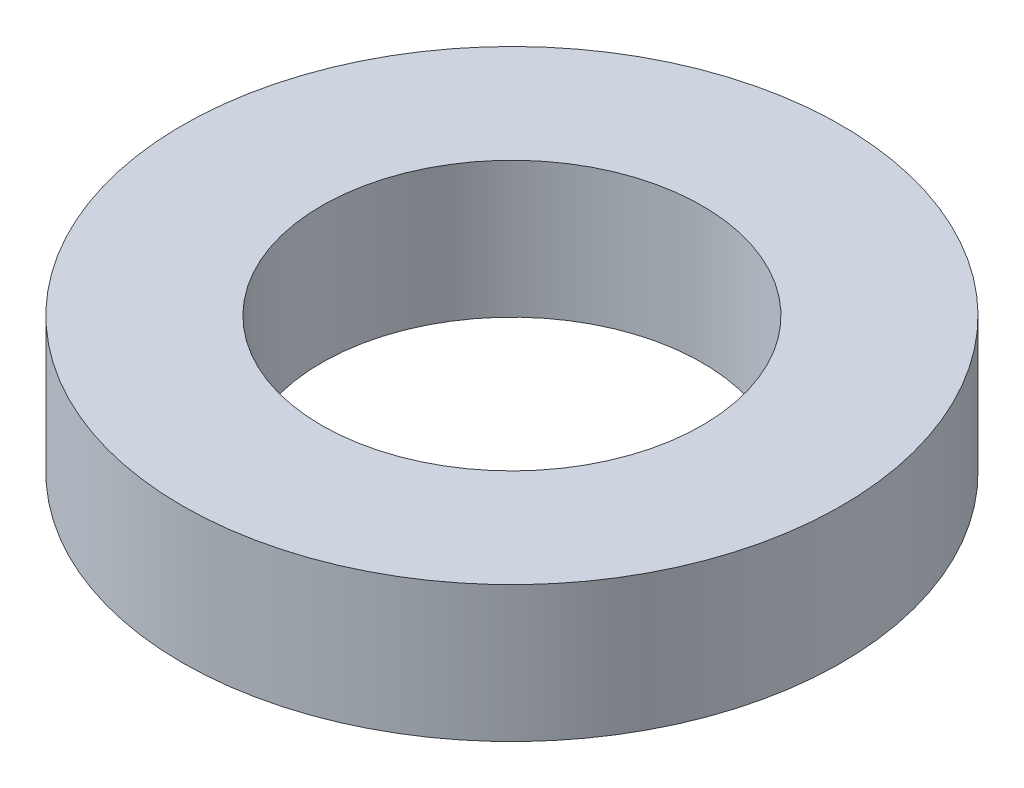
SolidWorks part; units mm, degrees
material "Rubber"
ref_plane "Front Plane" through (0, 0, 0) normal (0, 0, 1) x (1, 0, 0)
ref_plane "Top Plane" through (0, 0, 0) normal (0, 1, 0) x (1, 0, 0)
ref_plane "Right Plane" through (0, 0, 0) normal (1, 0, 0) x (0, 0, -1)
other "Configuration Table"
sketch "Sketch1" plane through (0, 0, 0) normal (0, 1, 0) x (1, 0, 0)
  circle A0 centre (0, 0) radius 2.8
  circle A1 centre (0, 0) radius 4.85
  dimension "D1" = 5.6
  dimension "D2" = 9.7
extrude "O_Ring" add sketch "Sketch1" along normal blind 2 from offset 1
equation "\"Jar_OD\"= 90  'ASSUMED - Part G fallback - jar outer diameter"
equation "\"Jar_H\"= 120  'ASSUMED - Part G fallback - jar height"
equation "\"Pump_L\"= 45  'ASSUMED - Part G fallback"
equation "\"Pump_W\"= 24  'ASSUMED - Part G fallback"
equation "\"Pump_H\"= 33  'ASSUMED - Part G fallback"
equation "\"Pump_Outlet_OD\"= 7.5  'ASSUMED - Part G fallback"
equation "\"Tube_OD\"= 8  'ASSUMED - Part G fallback"
equation "\"Tube_ID\"= 6  'ASSUMED - Part G fallback"
equation "\"TDS_Body_Dia\"= 12  'ASSUMED - Part G fallback"
equation "\"TDS_Wet_Len\"= 45  'ASSUMED - Part G fallback - length in water"
equation "\"DS_Tube_Dia\"= 6  'ASSUMED - Part G fallback"
equation "\"DS_Tube_Len\"= 50  'ASSUMED - Part G fallback"
equation "\"ORP_Body_Dia\"= 12  'ASSUMED - Part G fallback"
equation "\"ORP_Body_Len\"= 150  'ASSUMED - Part G fallback"
equation "\"ORP_Cap_Dia\"= 16  'ASSUMED - Part G fallback"
equation "\"Turb_W\"= 33  'ASSUMED - Part G fallback - head width"
equation "\"Turb_D\"= 28  'ASSUMED - Part G fallback - head depth"
equation "\"Turb_H\"= 30  'ASSUMED - Part G fallback - head height"
equation "\"Turb_Slot_W\"= 10  'ASSUMED - Part G fallback - slot width"
equation "\"Flow_L\"= 62  'ASSUMED - Part G fallback YF-S201"
equation "\"Flow_W\"= 36  'ASSUMED - Part G fallback"
equation "\"Flow_H\"= 35  'ASSUMED - Part G fallback"
equation "\"Thread_G12_OD\"= 20.955  'ASSUMED - Part G fallback thread G1/2 (major diameter)"
equation "\"Valve_L\"= 75  'ASSUMED - Part G fallback"
equation "\"Valve_W\"= 45  'ASSUMED - Part G fallback"
equation "\"Valve_H\"= 60  'ASSUMED - Part G fallback"
equation "\"Tee_L\"= 40  'ASSUMED - Part G fallback - overall length"
equation "\"Tee_Branch_L\"= 25  'ASSUMED - Part G fallback"
equation "\"Tee_OD\"= 12  'ASSUMED - Part G fallback"
equation "\"Cuv_W\"= 12.5  'ASSUMED - old R3 cuvette (station suppressed in SS4)"
equation "\"Cuv_D\"= 12.5  'ASSUMED - old R3 cuvette (station suppressed in SS4)"
equation "\"Cuv_H\"= 45  'ASSUMED - old R3 cuvette (station suppressed in SS4)"
equation "\"LED_Board_L\"= 20  'ASSUMED - Part G fallback"
equation "\"LED_Board_W\"= 20  'ASSUMED - Part G fallback - LED at centre"
equation "\"GUVA_L\"= 20  'ASSUMED - Part G fallback"
equation "\"GUVA_W\"= 12  'ASSUMED - Part G fallback - sensor at centre"
equation "\"Reed_L\"= 27  'ASSUMED - Part G fallback MC-38 half"
equation "\"Reed_W\"= 14  'ASSUMED - Part G fallback"
equation "\"Reed_H\"= 8  'ASSUMED - Part G fallback"
equation "\"ESP_L\"= 51  'ASSUMED - Part G fallback"
equation "\"ESP_W\"= 28  'ASSUMED - Part G fallback"
equation "\"TFT_L\"= 58  'ASSUMED - Part G fallback - board"
equation "\"TFT_W\"= 35  'ASSUMED - Part G fallback - board"
equation "\"TFT_Win_L\"= 35  'ASSUMED - Part G fallback - visible window"
equation "\"TFT_Win_W\"= 28  'ASSUMED - Part G fallback - visible window"
equation "\"Relay_L\"= 50  'ASSUMED - Part G fallback"
equation "\"Relay_W\"= 26  'ASSUMED - Part G fallback"
equation "\"Relay_H\"= 19  'ASSUMED - Part G fallback"
equation "\"Mosfet_L\"= 34  'ASSUMED - Part G fallback"
equation "\"Mosfet_W\"= 17  'ASSUMED - Part G fallback"
equation "\"Mosfet_H\"= 12  'ASSUMED - Part G fallback"
equation "\"TDS_Board_L\"= 42  'ASSUMED - Part G fallback"
equation "\"TDS_Board_W\"= 32  'ASSUMED - Part G fallback"
equation "\"Turb_Board_L\"= 38  'ASSUMED - Part G fallback"
equation "\"Turb_Board_W\"= 28  'ASSUMED - Part G fallback"
equation "\"BNC_Thread_Dia\"= 9.5  'ASSUMED - Part G fallback"
equation "\"Plate_L\"= 420  'ASSUMED - Part G fallback"
equation "\"Plate_W\"= 297  'ASSUMED - Part G fallback"
equation "\"Plate_T\"= 6  'ASSUMED - Part G fallback"
equation "\"Probe_Clr\"= 0.3  'DESIGN VALUE - Part C rule 3 - printed probe hole = diameter + 0.3"
equation "\"Cuv_Clr\"= 0.2  'DESIGN VALUE - Part C rule 3 - cuvette pocket = size + 0.2"
equation "\"Label_H\"= 0.6  'DESIGN VALUE - Part D - raised label height"
equation "\"Booster_L\"= 150  'ASSUMED - Part G fallback - booster pump"
equation "\"Booster_W\"= 95  'ASSUMED - Part G fallback"
equation "\"Booster_H\"= 100  'ASSUMED - Part G fallback"
equation "\"PTube_OD\"= 6.35  'ASSUMED - Part G fallback - product tube 1/4 inch"
equation "\"Qz_Out\"= 12  'ASSUMED - Part G fallback - quartz channel outside square"
equation "\"Qz_Path\"= 10  'ASSUMED - Part G fallback - quartz channel inside light path"
equation "\"Qz_L\"= 40  'ASSUMED - Part G fallback - quartz channel length"
equation "\"LED860_Dia\"= 5  'ASSUMED - Part G fallback - 860 nm LED"
equation "\"BPW_L\"= 5.4  'ASSUMED - Part G fallback - BPW34"
equation "\"BPW_W\"= 4.3  'ASSUMED - Part G fallback - BPW34"
equation "\"Cart_Dia\"= 50  'ASSUMED - Part G fallback - sediment and pre-carbon cartridges"
equation "\"Cart_L\"= 255  'ASSUMED - Part G fallback"
equation "\"UF_Dia\"= 50  'ASSUMED - Part G fallback - UF cartridge"
equation "\"UF_L\"= 260  'ASSUMED - Part G fallback"
equation "\"RO_Dia\"= 62  'ASSUMED - Part G fallback - RO membrane housing"
equation "\"RO_L\"= 300  'ASSUMED - Part G fallback"
equation "\"UVC_Dia\"= 40  'ASSUMED - Part G fallback - UV-C chamber"
equation "\"UVC_L\"= 300  'ASSUMED - Part G fallback"
equation "\"Tank_W\"= 260  'ASSUMED - Part G fallback - storage tank"
equation "\"Tank_D\"= 160  'ASSUMED - Part G fallback"
equation "\"Tank_H\"= 300  'ASSUMED - Part G fallback"
equation "\"Cab_W\"= 400  'ASSUMED - Part G fallback - purifier cabinet"
equation "\"Cab_D\"= 270  'ASSUMED - Part G fallback"
equation "\"Cab_H\"= 560  'ASSUMED - Part G fallback"
equation "\"ORP_Board_L\"= 40  'ASSUMED - Part G fallback - ORP buffer board"
equation "\"ORP_Board_W\"= 30  'ASSUMED - Part G fallback"
equation "\"Opt_Board_L\"= 50  'ASSUMED - Part G fallback - optical front-end board"
equation "\"Opt_Board_W\"= 40  'ASSUMED - Part G fallback"
equation "\"Buck_L\"= 43  'ASSUMED - Part G fallback - 12 V to 5 V buck module"
equation "\"Buck_W\"= 21  'ASSUMED - Part G fallback"
equation "\"Buck_H\"= 14  'ASSUMED - Part G fallback"
equation "\"BB_L\"= 165  'ASSUMED - Part G fallback - breadboard (As_Built_R3 only)"
equation "\"BB_W\"= 55  'ASSUMED - Part G fallback"
equation "\"BB_H\"= 10  'ASSUMED - Part G fallback"
